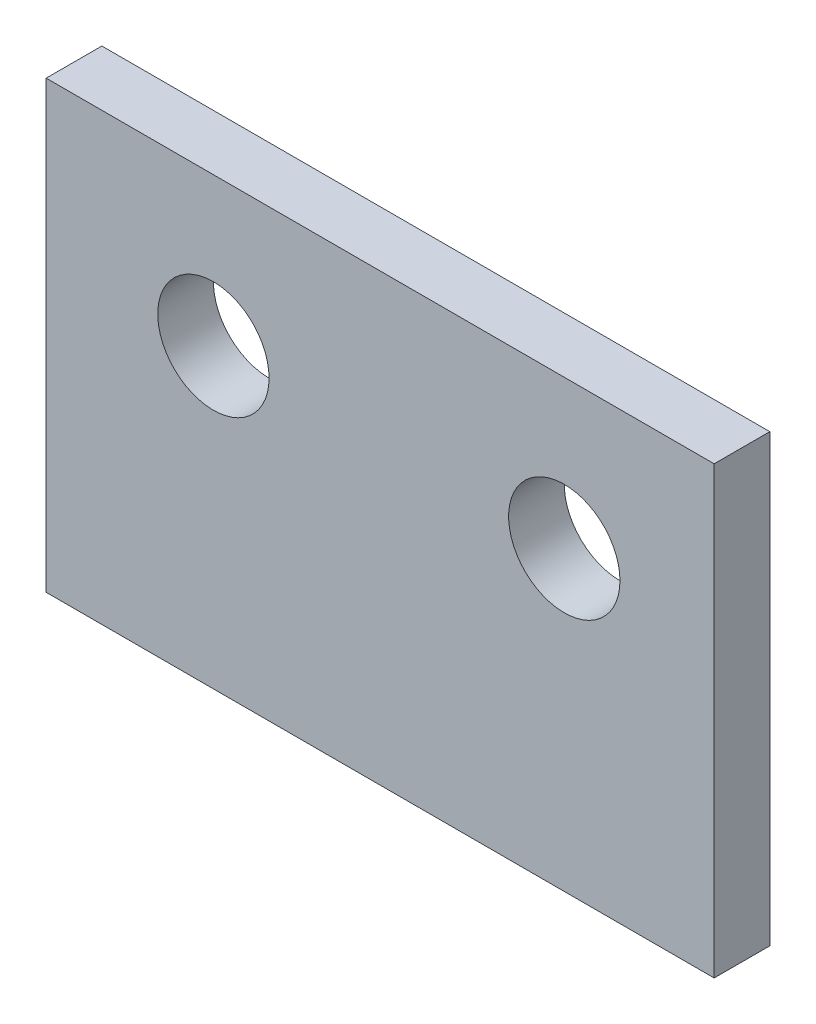
SolidWorks part; units mm, degrees
ref_plane "Front Plane" through (0, 0, 0) normal (0, 0, 1) x (1, 0, 0)
ref_plane "Top Plane" through (0, 0, 0) normal (0, 1, 0) x (1, 0, 0)
ref_plane "Right Plane" through (0, 0, 0) normal (1, 0, 0) x (0, 0, -1)
sketch "Sketch1" plane through (0, 0, 0) normal (0, 0, 1) x (1, 0, 0)
  line L1 (0, 0) -> (60, 0)
  line L2 (0, 0) -> (0, 40)
  line L3 (0, 40) -> (60, 40)
  line L4 (60, 0) -> (60, 40)
  circle A0 centre (15.0205, 26.6758) radius 5
  circle A1 centre (46.539, 26.6758) radius 5
  dimension "D3" = 10
  dimension "D1" = 60
  dimension "D2" = 40
extrude "Boss-Extrude1" add sketch "Sketch1" along normal blind 5 contours A0 | L2 L1 L4 L3 | A1
